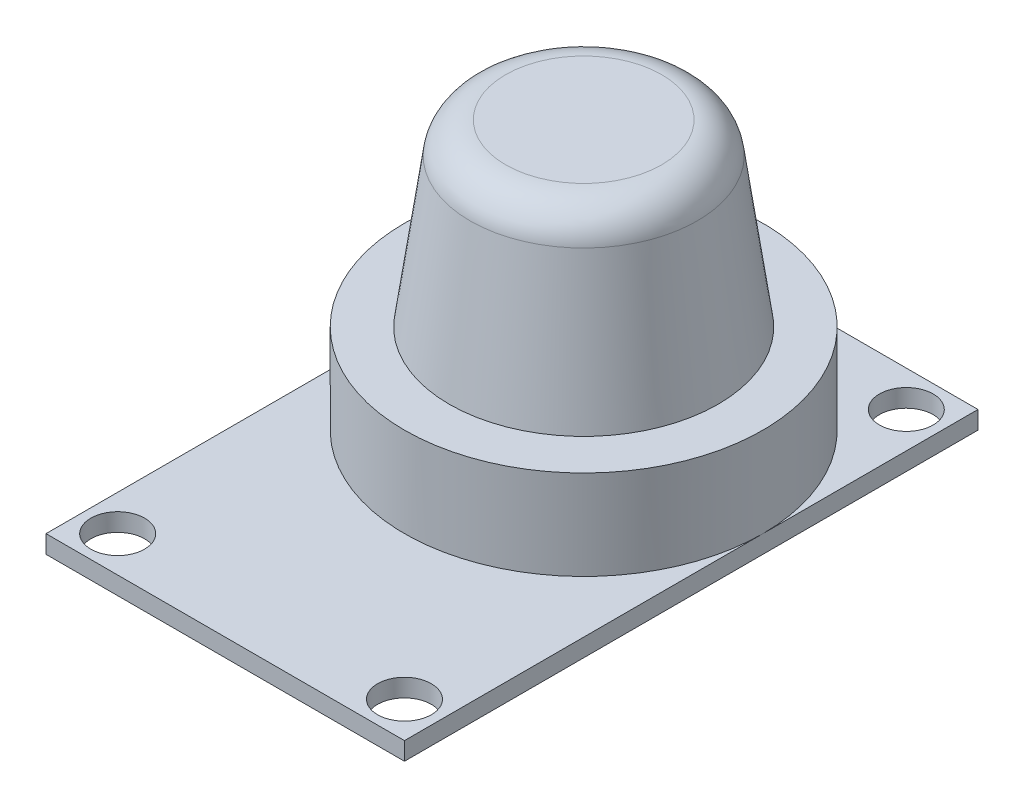
SolidWorks part; units mm, degrees
ref_plane "Front" through (0, 0, 0) normal (0, 0, 1) x (1, 0, 0)
ref_plane "Top" through (0, 0, 0) normal (0, 1, 0) x (1, 0, 0)
ref_plane "Right" through (0, 0, 0) normal (1, 0, 0) x (0, 0, -1)
sketch "Sketch1" plane through (0, 0, 0) normal (0, 1, 0) x (1, 0, 0)
  line L1 (-10, 16) -> (10, 16)
  line L2 (-10, 16) -> (-10, -16)
  line L3 (-10, -16) -> (10, -16)
  line L4 (10, 16) -> (10, -16)
  line L5 (-10, 16) -> (10, -16) construction
  line L6 (-10, -16) -> (10, 16) construction
  point P0 (0, 0)
  dimension "D1" = 32
  dimension "D2" = 20
extrude "Boss-Extrude1" add sketch "Sketch1" along normal blind 1
sketch "Sketch2" plane through (0, 1, 0) normal (0, 1, 0) x (1, 0, 0)
  circle A0 centre (0, 4) radius 10
  dimension "D2" = 20
  dimension "D1" = 4
extrude "Boss-Extrude2" add sketch "Sketch2" along normal blind 5
sketch "Sketch3" plane through (0, 1, 0) normal (0, 1, 0) x (1, 0, 0)
  line L0 (-10, 16) -> (-10, 4) construction
  line L2 (10, 16) -> (-10, 16) construction
  line L3 (10, 4) -> (10, 16) construction
  line L4 (-50, 0) -> (50, 0) construction
  circle A0 centre (8, 14) radius 1.5
  circle A1 centre (-8, 14) radius 1.5
  circle A2 centre (8, -14) radius 1.5
  circle A3 centre (-8, -14) radius 1.5
  dimension "D1" = 3
  dimension "D2" = 3
  dimension "D3" = 2
  dimension "D4" = 2
  dimension "D5" = 2
  dimension "D6" = 2
extrude "Cut-Extrude1" cut sketch "Sketch3" against normal blind 5
sketch "Sketch4" plane through (0, 6, 0) normal (0, 1, 0) x (1, 0, 0)
  circle A0 centre (0, 4) radius 7.5
  dimension "D1" = 15
extrude "Boss-Extrude3" add sketch "Sketch4" along normal blind 10 draft 8
fillet "Fillet1" radius 2 1 edges at (0, 16, 2.0946)
